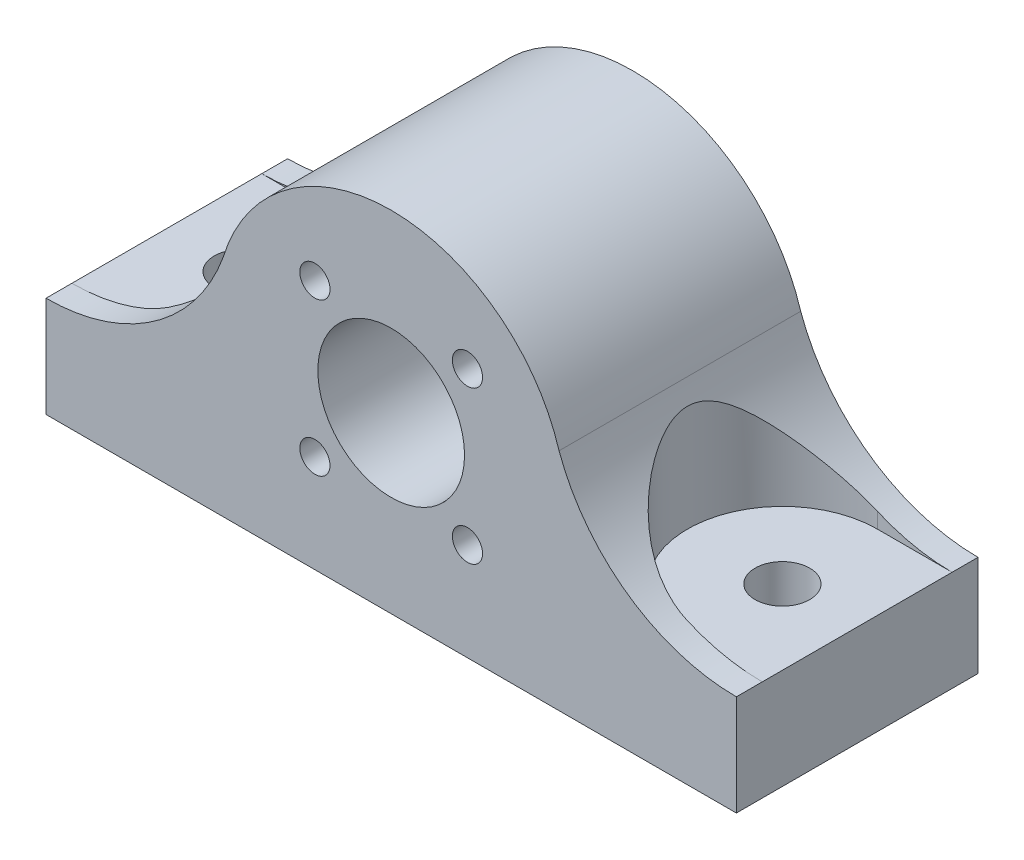
SolidWorks part; units mm, degrees
ref_plane "Alzado" through (0, 0, 0) normal (0, 0, 1) x (1, 0, 0)
ref_plane "Planta" through (0, 0, 0) normal (0, 1, 0) x (1, 0, 0)
ref_plane "Vista lateral" through (0, 0, 0) normal (1, 0, 0) x (0, 0, -1)
sketch "Croquis2" plane through (0, 0, 0) normal (0, 0, 1) x (1, 0, 0)
  line L0 (-24, 17.3) -> (24, 17.3) construction
  line L1 (24, 0) -> (-24, 0) construction
  line L2 (24, 0) -> (24, -7)
  line L3 (24, -7) -> (-24, -7)
  line L4 (-24, 0) -> (-24, -7)
  arc A0 (-11.6721, 8.65) -> (11.6721, 8.65) centre (0, 5.1) cw
  arc A1 (-24, 0) -> (-11.6721, 8.65) centre (-24, 13.1098) ccw
  arc A2 (24, 0) -> (11.6721, 8.65) centre (24, 13.1098) cw
  circle A3 centre (0, 5.1) radius 5.1
  dimension "D3" = 24.3
  dimension "D4" = 10.2
  dimension "D1" = 48
  dimension "D2" = 7
  dimension "D5" = 8.65
extrude "Saliente-Extruir1" add sketch "Croquis2" along normal blind 16.8
sketch "Croquis3" plane through (0, 0, 16.8) normal (0, 0, 1) x (1, 0, 0)
  line L0 (0, 5.1) -> (5.3033, 10.4033) construction
  line L1 (0, 5.1) -> (7.5, 5.1) construction
  circle A0 centre (0, 5.1) radius 7.5 construction
  circle A1 centre (0, 5.1) radius 5.1 construction
  circle A2 centre (5.3033, 10.4033) radius 1.05
  circle A3 centre (5.3033, -0.2033) radius 1.05
  circle A4 centre (-5.3033, -0.2033) radius 1.05
  circle A5 centre (-5.3033, 10.4033) radius 1.05
  point P16 (0, 5.1)
  dimension "D1" = 15
  dimension "D2" = 2.1
  dimension "D3" = 45
  dimension "D4" = 4
extrude "Cortar-Extruir1" cut sketch "Croquis3" against normal through all
sketch "Croquis4" plane through (0, 0, 0) normal (0, 1, 0) x (1, 0, 0)
  line L0 (-24, -1.8) -> (-24, -15)
  line L1 (-24, -16.8) -> (-24, 0) construction
  line L2 (-24, -15) -> (-18.8, -15)
  line L3 (-24, -1.8) -> (-18.8, -1.8)
  line L4 (-11.6721, 0) -> (-24, 0) construction
  line L5 (-24, -16.8) -> (-11.6721, -16.8) construction
  line L6 (0, 0) -> (0, -16.8) construction
  line L7 (-11.6721, -16.8) -> (11.6721, -16.8) construction
  line L8 (24, -15) -> (18.8, -15)
  line L9 (24, -1.8) -> (24, -15)
  line L10 (24, -1.8) -> (18.8, -1.8)
  arc A0 (-18.8, -1.8) -> (-18.8, -15) centre (-18.8, -8.4) cw
  arc A1 (18.8, -1.8) -> (18.8, -15) centre (18.8, -8.4) ccw
  dimension "D1" = 1.8
  dimension "D2" = 1.8
  dimension "D3" = 5.2
extrude "Cortar-Extruir2" cut sketch "Croquis4" along normal through all
sketch "Croquis5" plane through (0, 0, 0) normal (0, 1, 0) x (1, 0, 0)
  line L2 (-11.6721, 0) -> (-24, 0) construction
  line L3 (-24, -1.8) -> (-24, -15) construction
  line L4 (0, 0) -> (0, -16.8) construction
  line L5 (-11.6721, -16.8) -> (11.6721, -16.8) construction
  circle A0 centre (-18.8, -8.4) radius 1.9
  circle A1 centre (18.8, -8.4) radius 1.9
  dimension "D1" = 3.8
  dimension "D2" = 8.4
  dimension "D3" = 5.2
extrude "Cortar-Extruir3" cut sketch "Croquis5" against normal through all
